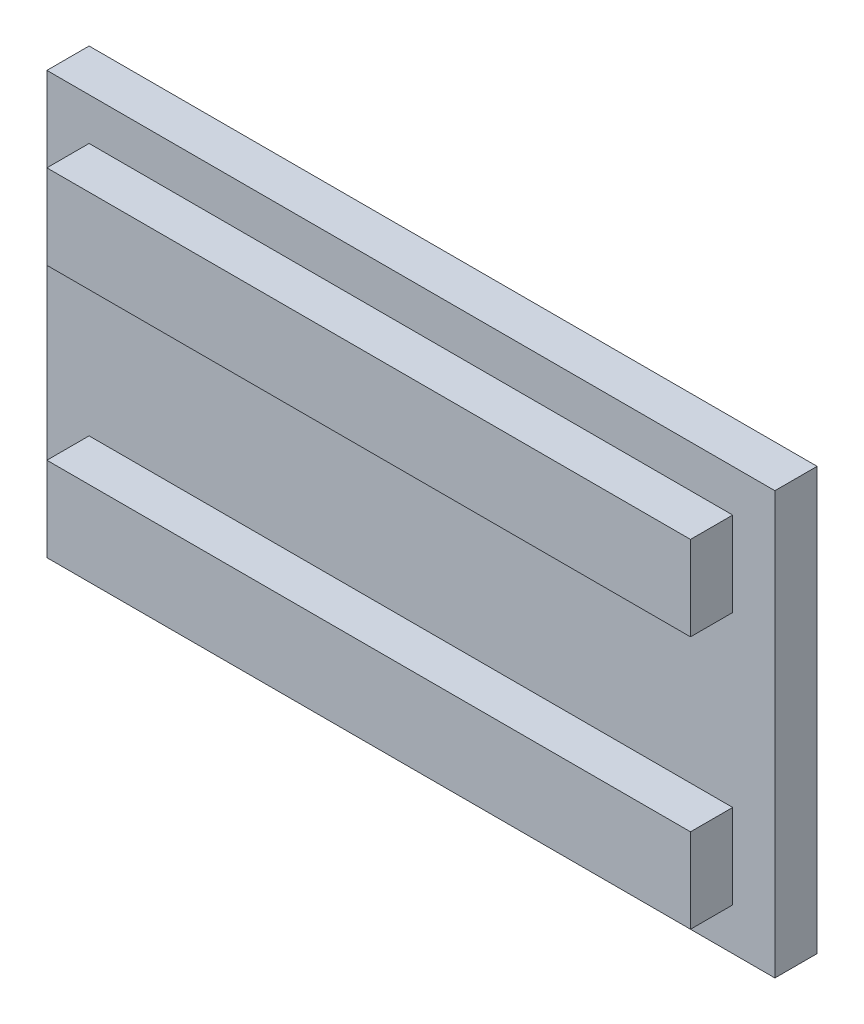
SolidWorks part; units mm, degrees
ref_plane "Ebene vorne" through (0, 0, 0) normal (0, 0, 1) x (1, 0, 0)
ref_plane "Ebene oben" through (0, 0, 0) normal (0, 1, 0) x (1, 0, 0)
ref_plane "Ebene rechts" through (0, 0, 0) normal (1, 0, 0) x (0, 0, -1)
sketch "Sketch1" plane through (0, 0, 0) normal (0, 0, 1) x (1, 0, 0)
  line L1 (-17.25, 10) -> (17.25, 10)
  line L2 (-17.25, 10) -> (-17.25, -10)
  line L3 (-17.25, -10) -> (17.25, -10)
  line L4 (17.25, 10) -> (17.25, -10)
  line L5 (-17.25, 10) -> (17.25, -10) construction
  line L6 (-17.25, -10) -> (17.25, 10) construction
  point P0 (0, 0)
  dimension "D1" = 34.5
  dimension "D2" = 20
extrude "Boss-Extrude1" add sketch "Sketch1" along normal blind 2
sketch "Sketch2" plane through (0, 0, 2) normal (0, 0, 1) x (1, 0, 0)
  line L0 (-15.25, 8) -> (-15.25, 4)
  line L1 (-17.25, 10) -> (17.25, 10) construction
  line L2 (-17.25, 10) -> (-17.25, -10) construction
  line L3 (-17.25, -10) -> (17.25, -10) construction
  line L4 (17.25, 10) -> (17.25, -10) construction
  line L5 (-17.25, 10) -> (17.25, -10) construction
  line L6 (-17.25, -10) -> (17.25, 10) construction
  line L7 (-15.25, -8) -> (15.25, -8)
  line L8 (15.25, 8) -> (15.25, 4)
  line L9 (-15.25, 8) -> (15.25, 8)
  line L10 (-15.25, -4) -> (15.25, -4)
  line L11 (-15.25, 4) -> (15.25, 4)
  line L12 (-15.25, -4) -> (-15.25, -8)
  line L13 (15.25, -4) -> (15.25, -8)
  line L14 (-15.25, 8) -> (-15.25, -8) construction
  line L16 (15.25, 8) -> (15.25, -8) construction
  point P0 (0, 0)
  dimension "D2" = 4
  dimension "D3" = 4
  dimension "D1" = 2
extrude "Boss-Extrude2" add sketch "Sketch2" along normal blind 2
